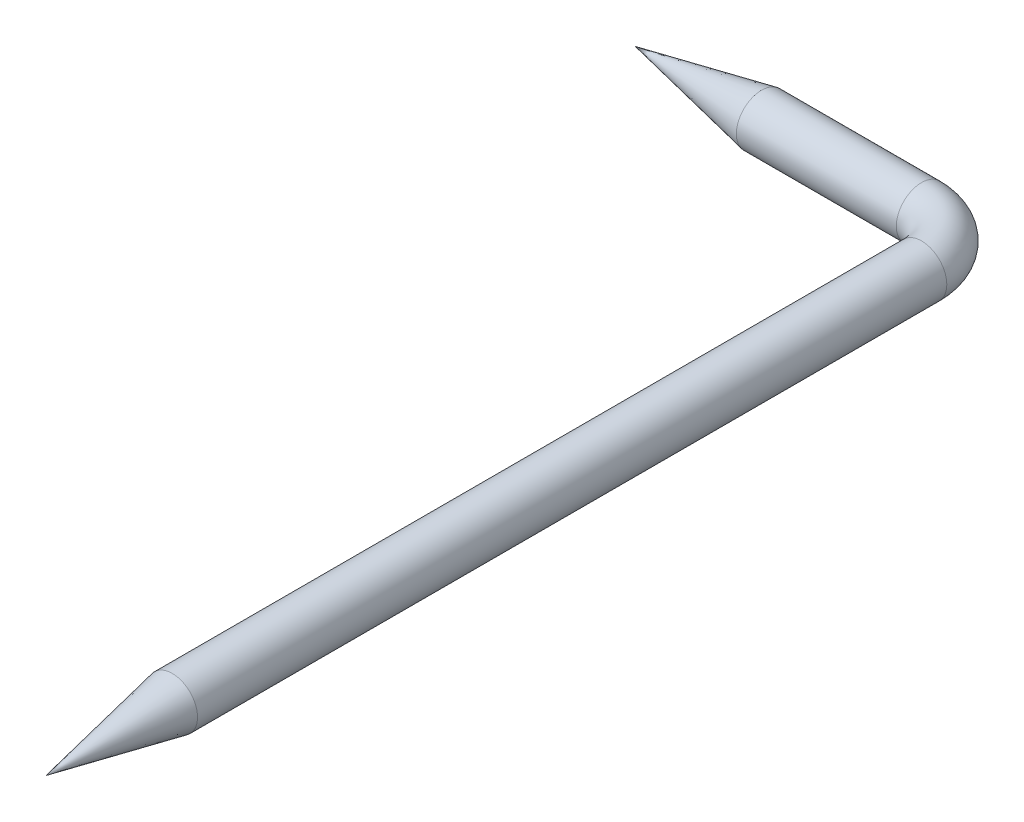
SolidWorks part; units mm, degrees
ref_plane "Front Plane" through (0, 0, 0) normal (0, 0, 1) x (1, 0, 0)
ref_plane "Top Plane" through (0, 0, 0) normal (0, 1, 0) x (1, 0, 0)
ref_plane "Right Plane" through (0, 0, 0) normal (1, 0, 0) x (0, 0, -1)
sketch "Sketch1" plane through (0, 0, 0) normal (0, 1, 0) x (1, 0, 0)
  line L0 (0, 0) -> (19, 0)
  line L1 (25, -6) -> (25, -95)
  arc A0 (19, 0) -> (25, -6) centre (19, -6) cw
  dimension "D1" = 6
sketch "Sketch2" plane through (0, 0, 0) normal (1, 0, 0) x (0, 0, -1)
  circle A0 centre (0, 0) radius 3
sweep "Sweep1" add profiles "Sketch2" path "Sketch1"
sketch "Sketch3" plane through (0, 0, 0) normal (0, 1, 0) x (1, 0, 0)
  line L0 (0, 0) -> (-15, 0)
  line L1 (-15, 0) -> (0, -3)
  line L2 (0, -3) -> (0, 0)
revolve "Revolve1" add sketch "Sketch3" angle 360 about L0
sketch "Sketch4" plane through (0, 0, 0) normal (0, 1, 0) x (1, 0, 0)
  line L0 (25, -95) -> (25, -110)
  line L1 (22, -95) -> (28, -95) construction
  line L2 (25, -110) -> (28, -95)
  line L3 (28, -95) -> (25, -95)
revolve "Revolve2" add sketch "Sketch4" angle 360 about L0
